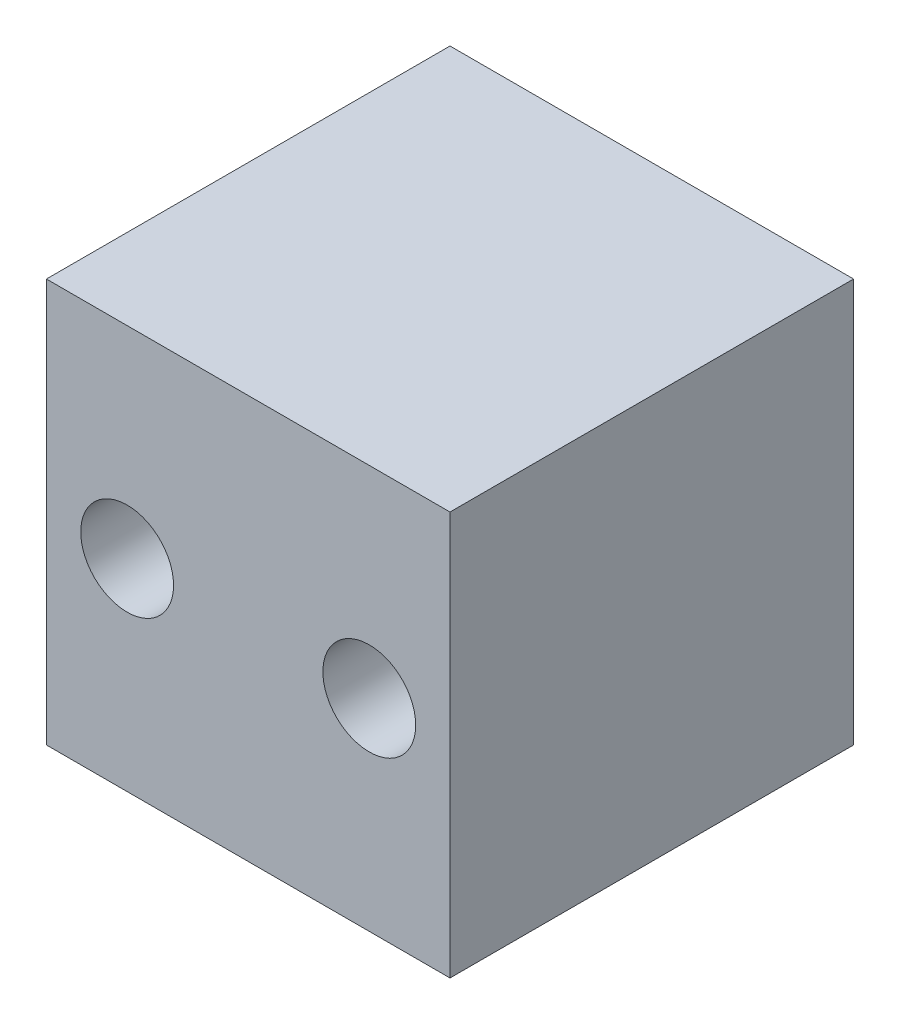
SolidWorks part; units mm, degrees
ref_plane "Ebene vorne" through (0, 0, 0) normal (0, 0, 1) x (1, 0, 0)
ref_plane "Ebene oben" through (0, 0, 0) normal (0, 1, 0) x (1, 0, 0)
ref_plane "Ebene rechts" through (0, 0, 0) normal (1, 0, 0) x (0, 0, -1)
sketch "Skizze1" plane through (0, 0, 0) normal (0, 0, 1) x (1, 0, 0)
  line L1 (50, -50) -> (-50, -50)
  line L2 (50, -50) -> (50, 50)
  line L3 (50, 50) -> (-50, 50)
  line L4 (-50, -50) -> (-50, 50)
  line L5 (50, -50) -> (-50, 50) construction
  line L6 (50, 50) -> (-50, -50) construction
  point P0 (0, 0)
  dimension "D1" = 100
extrude "Aufsatz-Linear austragen1" add sketch "Skizze1" along normal blind 100
hole_wizard "Stirnsenkung für M8 Senkschraube (Kopf Button)1" positions "Skizze3" profile "Skizze2" counterbore size "M8" standard "ANSI Metrisch" end condition through all
sketch "Skizze3" plane through (0, 0, 100) normal (0, 0, 1) x (1, 0, 0)
  line L0 (50, 50) -> (-50, 50) construction
  line L1 (-50, 50) -> (-50, -50) construction
  point P0 (-30, 0)
  point P5 (-50, 0)
  dimension "D1" = 50
  dimension "D2" = 20
sketch "Skizze2" plane through (-30, 0, 100) normal (1, 0, 0) x (0, -1, 0)
  line L0 (0, 0) -> (0, 100)
  line L1 (0, 100) -> (4.5, 100)
  line L3 (4.5, 100) -> (4.5, 90)
  line L4 (4.5, 90) -> (11.5, 90)
  line L5 (11.5, 90) -> (11.5, 0)
  line L7 (11.5, 0) -> (0, 0)
  line L11 (0, -6.35) -> (0, 107.95) construction
  dimension "Bohrerdurchmesser" = 9
  dimension "Bohrungstiefe" = 100
  dimension "Senkdurchmesser2" = 23
  dimension "Senktiefe2" = 90
mirror "Spiegeln1" about plane through (0, 0, 0) normal (1, 0, 0) of "Stirnsenkung für M8 Senkschraube (Kopf Button)1"
